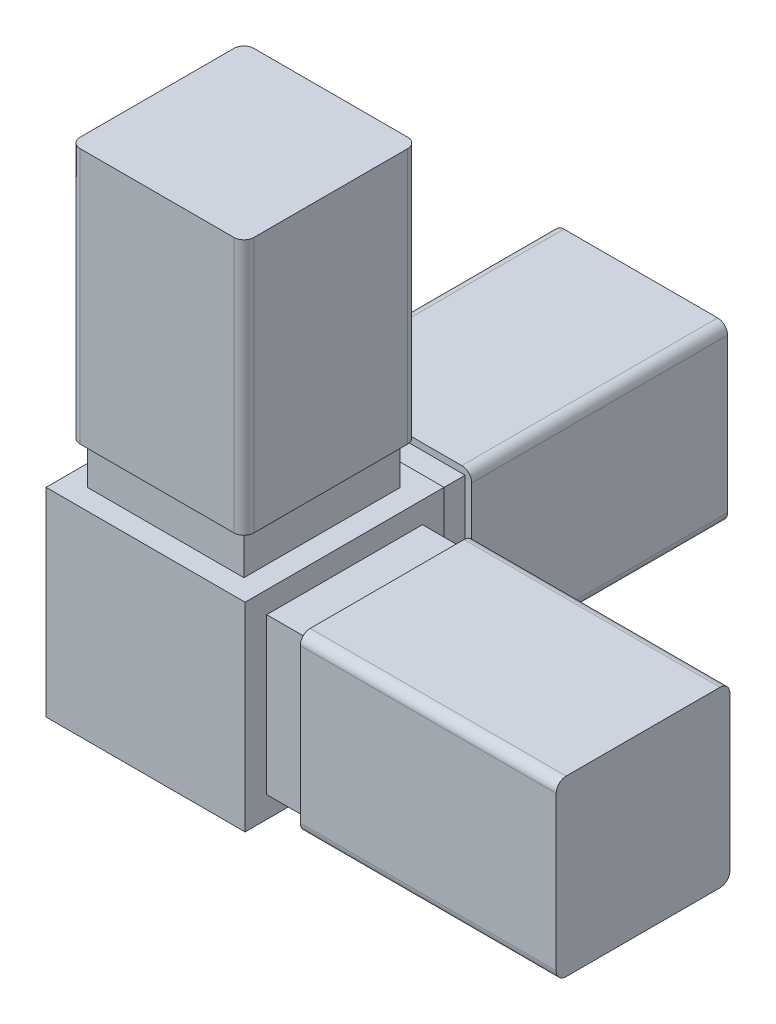
SolidWorks part; units mm, degrees
ref_plane "Płaszczyzna przednia" through (0, 0, 0) normal (0, 0, 1) x (1, 0, 0)
ref_plane "Płaszczyzna górna" through (0, 0, 0) normal (0, 1, 0) x (1, 0, 0)
ref_plane "Płaszczyzna prawa" through (0, 0, 0) normal (1, 0, 0) x (0, 0, -1)
sketch "Szkic1" plane through (0, 0, 0) normal (0, 0, 1) x (1, 0, 0)
  line L1 (-13.9172, 29.2261) -> (6.0828, 29.2261)
  line L2 (-13.9172, 29.2261) -> (-13.9172, 9.2261)
  line L3 (-13.9172, 9.2261) -> (6.0828, 9.2261)
  line L4 (6.0828, 29.2261) -> (6.0828, 9.2261)
  dimension "D1" = 20
  dimension "D2" = 20
extrude "Dodanie-wyciągnięcie1" add sketch "Szkic1" along normal blind 20
sketch "Szkic2" plane through (0, 29.2261, 0) normal (0, 1, 0) x (1, 0, 0)
  line L0 (-13.9172, 0) -> (6.0828, -20) construction
  line L1 (6.0828, 0) -> (-13.9172, -20) construction
  line L2 (-11.8071, -2.2286) -> (3.8929, -2.2286)
  line L3 (3.8929, -2.2286) -> (3.8929, -17.9286)
  line L4 (3.8929, -17.9286) -> (-11.8071, -17.9286)
  line L5 (-11.8071, -2.2286) -> (3.8929, -17.9286) construction
  line L6 (-11.8071, -2.2286) -> (-11.8071, -17.9286)
  line L7 (-11.8071, -17.9286) -> (3.8929, -2.2286) construction
  circle A0 centre (-3.9172, -10) radius 11.0745 construction
  dimension "D1" = 15.7
  dimension "D2" = 15.7
extrude "Dodanie-wyciągnięcie2" add sketch "Szkic2" along normal blind 4.28
sketch "Szkic3" plane through (6.0828, 0, 0) normal (1, 0, 0) x (0, 0, -1)
  line L0 (-20, 29.2261) -> (0, 9.2261) construction
  line L1 (0, 29.2261) -> (-20, 9.2261) construction
  line L2 (-2.1688, 11.3949) -> (-2.1688, 27.0574)
  line L3 (-2.1688, 27.0574) -> (-17.8312, 27.0574)
  line L4 (-17.8312, 27.0574) -> (-17.8312, 11.3949)
  line L5 (-17.8312, 11.3949) -> (-2.1688, 11.3949)
  circle A0 centre (-10, 19.2261) radius 11.075 construction
extrude "Dodanie-wyciągnięcie3" add sketch "Szkic3" along normal blind 4.28
sketch "Szkic4" plane through (0, 0, 0) normal (0, 0, -1) x (-1, 0, 0)
  line L0 (-6.0828, 29.2261) -> (13.9172, 9.2261) construction
  line L1 (13.9172, 29.2261) -> (-6.0828, 9.2261) construction
  line L2 (11.7484, 27.0574) -> (11.7484, 11.3949)
  line L3 (11.7484, 11.3949) -> (-3.914, 11.3949)
  line L4 (-3.914, 11.3949) -> (-3.914, 27.0574)
  line L5 (-3.914, 27.0574) -> (11.7484, 27.0574)
  circle A0 centre (3.9172, 19.2261) radius 11.075 construction
extrude "Dodanie-wyciągnięcie4" add sketch "Szkic4" along normal blind 4.28
sketch "Szkic5" plane through (0, 0, -4.28) normal (0, 0, -1) x (-1, 0, 0)
  line L0 (-4.5828, 27.7261) -> (11.7484, 11.3949) construction
  line L1 (-3.914, 27.0574) -> (-3.914, 11.3949) construction
  line L2 (11.7484, 11.3949) -> (11.7484, 27.0574) construction
  line L3 (11.7484, 27.0574) -> (-3.914, 11.3949) construction
  line L4 (-3.914, 11.3949) -> (11.7484, 11.3949) construction
  line L5 (-4.5828, 8.2763) -> (-4.5828, 34.8251) construction
  line L6 (-4.5828, 27.7261) -> (12.8725, 27.7261)
  line L7 (12.8725, 27.7261) -> (12.8725, 10.2708)
  line L8 (12.8725, 10.2708) -> (-4.5828, 10.2708)
  line L9 (-4.5828, 10.2708) -> (-4.5828, 27.7261)
  circle A0 centre (4.1449, 18.9985) radius 12.3428 construction
  dimension "D1" = 24.6856
extrude "Dodanie-wyciągnięcie5" add sketch "Szkic5" along normal blind 25.72
sketch "Szkic6" plane through (10.3628, 0, 0) normal (1, 0, 0) x (0, 0, -1)
  line L0 (-18.7292, 27.9554) -> (-1.2708, 10.4969) construction
  line L2 (-18.7292, 27.9554) -> (-1.2708, 27.9554)
  line L3 (-1.2708, 27.9554) -> (-1.2708, 10.4969)
  line L4 (-1.2708, 10.4969) -> (-18.7292, 10.4969)
  line L5 (-18.7292, 10.4969) -> (-18.7292, 27.9554)
  circle A0 centre (-10, 19.2261) radius 12.345 construction
extrude "Dodanie-wyciągnięcie6" add sketch "Szkic6" along normal blind 25.72
sketch "Szkic7" plane through (0, 33.5061, 0) normal (0, 1, 0) x (1, 0, 0)
  line L0 (-12.6863, -18.8078) -> (4.7722, -1.3493) construction
  line L1 (-12.6863, -18.8078) -> (-12.6863, -1.3493)
  line L2 (-12.6863, -1.3493) -> (4.7722, -1.3493)
  line L3 (4.7722, -1.3493) -> (4.7722, -18.8078)
  line L4 (4.7722, -18.8078) -> (-12.6863, -18.8078)
  circle A0 centre (-3.9571, -10.0786) radius 12.345 construction
extrude "Dodanie-wyciągnięcie7" add sketch "Szkic7" along normal blind 25.72
fillet "Zaokrąglenie2" radius 1 12 edges at (23.2228, 27.9554, 18.7292) (23.2228, 27.9554, 1.2708) (23.2228, 10.4969, 1.2708) (23.2228, 10.4969, 18.7292) (-12.8725, 10.2708, -17.14) (-12.8725, 27.7261, -17.14) (4.5828, 10.2708, -17.14) (4.5828, 27.7261, -17.14) (4.7722, 46.3661, 1.3493) (4.7722, 46.3661, 18.8078) (-12.6863, 46.3661, 18.8078) (-12.6863, 46.3661, 1.3493)
